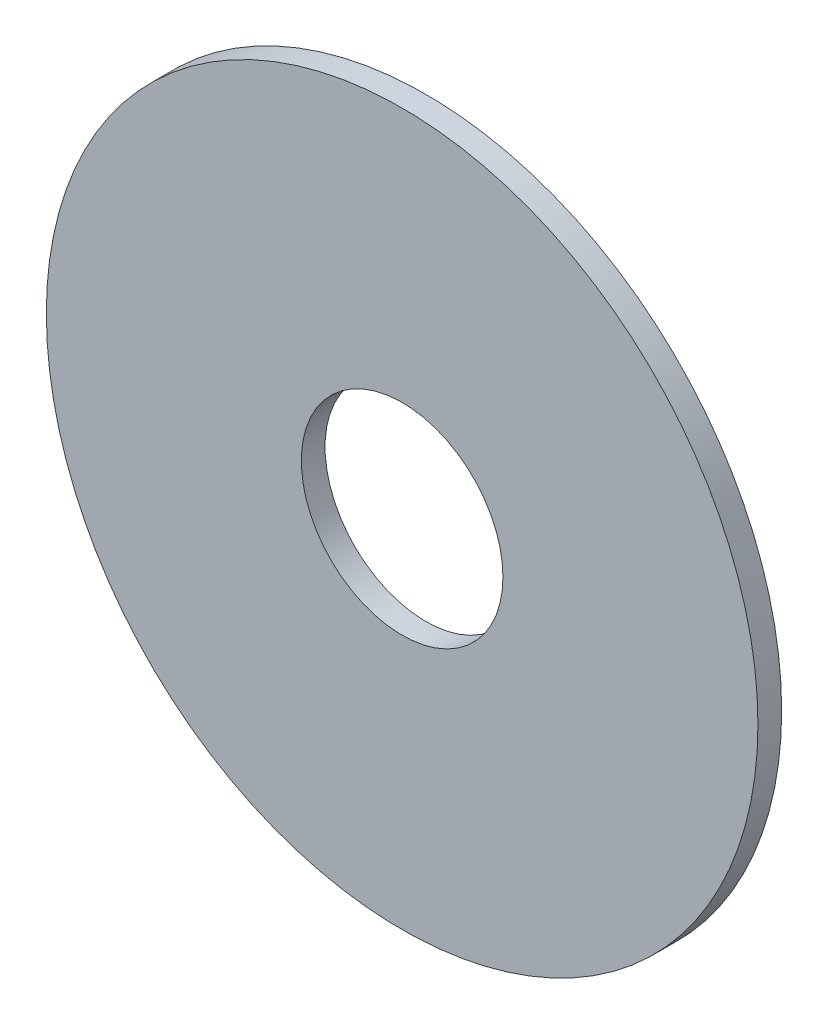
SolidWorks part; units mm, degrees
material "PA Type 6"
ref_plane "Front Plane" through (0, 0, 0) normal (0, 0, 1) x (1, 0, 0)
ref_plane "Top Plane" through (0, 0, 0) normal (0, 1, 0) x (1, 0, 0)
ref_plane "Right Plane" through (0, 0, 0) normal (1, 0, 0) x (0, 0, -1)
sketch "Sketch1" plane through (0, 0, 0) normal (0, 0, 1) x (1, 0, 0)
  circle A0 centre (0, 0) radius 4 construction
  circle A1 centre (0, 0) radius 15
  circle A2 centre (0, 0) radius 4.25
  dimension "D1" = 8
  dimension "D2" = 30
  dimension "D3" = 0.25
extrude "Boss-Extrude1" add sketch "Sketch1" along normal blind 1
